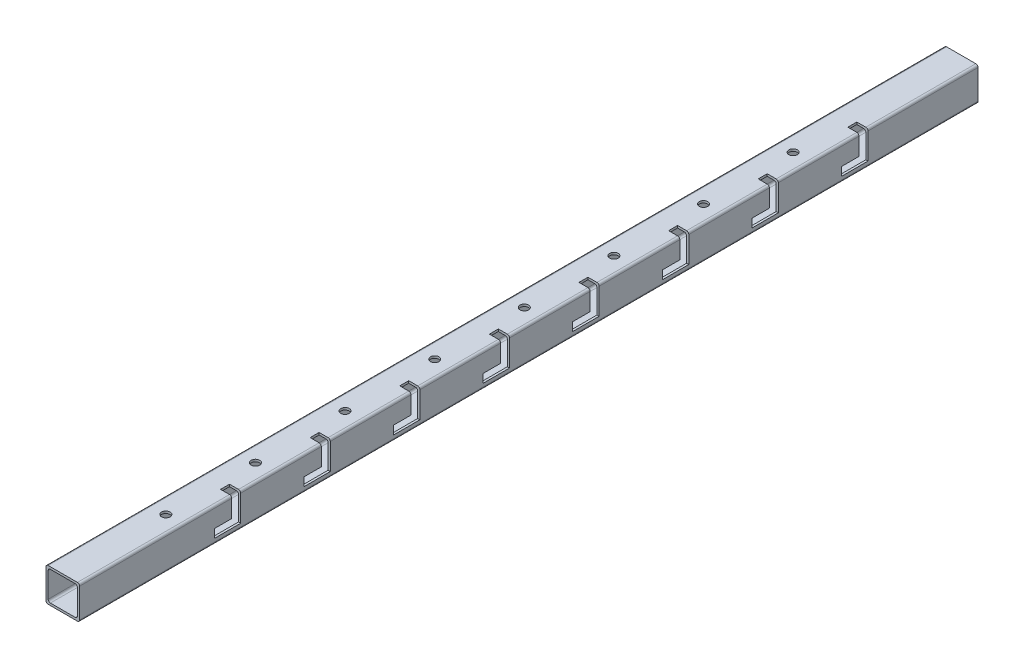
SolidWorks part; units mm, degrees
ref_plane "Front Plane" through (0, 0, 0) normal (0, 0, 1) x (1, 0, 0)
ref_plane "Top Plane" through (0, 0, 0) normal (0, 1, 0) x (1, 0, 0)
ref_plane "Right Plane" through (0, 0, 0) normal (1, 0, 0) x (0, 0, -1)
sketch "Sketch1" plane through (0, 0, 0) normal (0, 0, 1) x (1, 0, 0)
  line L0 (-9.525, 0) -> (9.525, 0) construction
  line L1 (0, -9.525) -> (0, 9.525) construction
  line L2 (8.2804, 0) -> (8.2804, 8.2804) construction
  line L3 (-9.525, -9.525) -> (9.525, -9.525) construction
  line L4 (-9.525, -9.525) -> (-9.525, 9.525) construction
  line L5 (-9.525, 9.525) -> (9.525, 9.525) construction
  line L6 (9.525, -9.525) -> (9.525, 9.525) construction
  line L7 (-9.525, -9.525) -> (9.525, 9.525) construction
  line L8 (-9.525, 9.525) -> (9.525, -9.525) construction
  line L9 (8.2804, 8.2804) -> (-8.2804, 8.2804) construction
  line L10 (-8.2804, 8.2804) -> (-8.2804, -8.2804) construction
  line L11 (-8.2804, -8.2804) -> (8.2804, -8.2804) construction
  line L12 (8.2804, -8.2804) -> (8.2804, 0) construction
  point P0 (0, 0)
  point P4 (0, 0)
  point P9 (0, 0)
  point P10 (8.2804, 0)
  point P13 (0, -8.2804)
  point P14 (-8.2804, 0)
  point P15 (0, 8.2804)
  dimension "Width" = 19.05
  dimension "Wall Thickness" = 1.2446
  dimension "Height" = 19.05
  dimension "D1" = 1.2446
  dimension "D2" = 1.2446
  dimension "D3" = 1.2446
sketch "Sketch2" plane through (0, 0, 0) normal (1, 0, 0) x (0, 0, -1)
  line L0 (254.635, 9.525) -> (-254.635, 9.525) construction
  point P3 (-232.7275, 9.525)
  point P5 (232.7275, 9.525)
  point P7 (0, 9.525)
  dimension "D1" = 21.9075
  dimension "D2" = 21.9075
  dimension "Length" = 509.27
sketch "Sketch3" plane through (0, 0, 0) normal (0, 0, 1) x (1, 0, 0)
  line L1 (9.525, 9.525) -> (-9.525, 9.525)
  line L2 (-9.525, 9.525) -> (-9.525, -9.525)
  line L3 (-9.525, -9.525) -> (9.525, -9.525) construction
  line L4 (-9.525, -9.525) -> (9.525, -9.525)
  line L5 (9.525, -9.525) -> (9.525, 9.525)
  line L6 (-8.2804, 8.2804) -> (8.2804, 8.2804)
  line L7 (8.2804, 8.2804) -> (8.2804, -8.2804)
  line L8 (8.2804, -8.2804) -> (-8.2804, -8.2804)
  line L9 (-8.2804, -8.2804) -> (-8.2804, 8.2804)
extrude "Boss-Extrude1" add sketch "Sketch3" along normal mid plane 509.27
fillet "Fillet1" radius 1.2446 8 edges at (-9.525, 9.525, 0) (8.2804, -8.2804, 0) (-8.2804, -8.2804, 0) (-8.2804, 8.2804, 0) (8.2804, 8.2804, 0) (9.525, -9.525, 0) (-9.525, -9.525, 0) (9.525, 9.525, 0)
sketch "Sketch4" plane through (0, 9.525, 0) normal (0, 1, 0) x (1, 0, 0)
  line L0 (0, 254.635) -> (0, 159.385) construction
  line L1 (8.2804, 254.635) -> (-8.2804, 254.635) construction
  line L2 (0, 159.385) -> (0, 108.585) construction
  circle A0 centre (0, 159.385) radius 2.413
  circle A1 centre (0, 108.585) radius 2.413
  circle A2 centre (0, 57.785) radius 2.413
  circle A3 centre (0, 6.985) radius 2.413
  circle A4 centre (0, -43.815) radius 2.413
  circle A5 centre (0, -94.615) radius 2.413
  circle A6 centre (0, -145.415) radius 2.413
  circle A7 centre (0, -196.215) radius 2.413
  dimension "D2" = 4.826
  dimension "D4" = 4.826
  dimension "D1" = 95.25
  dimension "D3" = 50.8
  dimension "D5" = 7
extrude "Cut-Extrude1" cut sketch "Sketch4" against normal up to next
sketch "Sketch6" plane through (-9.525, 0, 0) normal (-1, 0, 0) x (0, 0, 1)
  line L0 (-254.635, 0) -> (-179.705, 0) construction
  line L1 (-254.635, 8.2804) -> (-254.635, -8.2804) construction
  line L2 (-182.118, -1.651) -> (-187.198, -1.651)
  line L7 (-182.118, -6.477) -> (-177.292, -1.651) construction
  line L12 (-177.292, -6.477) -> (-182.118, -6.477)
  line L13 (-177.292, -6.477) -> (-177.292, -1.651)
  line L14 (-177.292, -1.651) -> (-182.118, -1.651)
  line L15 (-182.118, -6.477) -> (-182.118, -1.651) construction
  line L16 (-192.278, 9.525) -> (-192.278, -6.477)
  line L17 (-177.292, -6.477) -> (-182.118, -1.651) construction
  line L18 (-254.635, 9.525) -> (254.635, 9.525) construction
  line L19 (-192.278, -6.477) -> (-182.118, -6.477)
  line L20 (-187.198, -1.651) -> (-187.198, 9.525)
  line L21 (-187.198, 9.525) -> (-192.278, 9.525)
  point P12 (-179.705, -4.064)
  dimension "D1" = 74.93
  dimension "D2" = 16.002
  dimension "D3" = 4.826
  dimension "D4" = 4.826
  dimension "D5" = 10.16
  dimension "D6" = 5.08
extrude "Cut-Extrude3" cut sketch "Sketch6" along normal blind 6.35 from surface at -19.05 starting at face at (9.525, 0, 0)
pattern_linear "LPattern2" count 8 spacing 50.8 along (0, 0, 1) of "Cut-Extrude3"
equation "\"D1@Boss-Extrude1\" = \"Length@Sketch2\""
equation "\"D1@Sketch2\" = \"Width@Sketch1\" * 1.15"
equation "\"D2@Sketch2\"=\"D1@Sketch2\""
equation "\"D1@Sketch1\"=\"Wall Thickness@Sketch1\""
equation "\"D2@Sketch1\"=\"Wall Thickness@Sketch1\""
equation "\"D3@Sketch1\"=\"Wall Thickness@Sketch1\""
equation "\"D1@Fillet1\"=\"Wall Thickness@Sketch1\""
